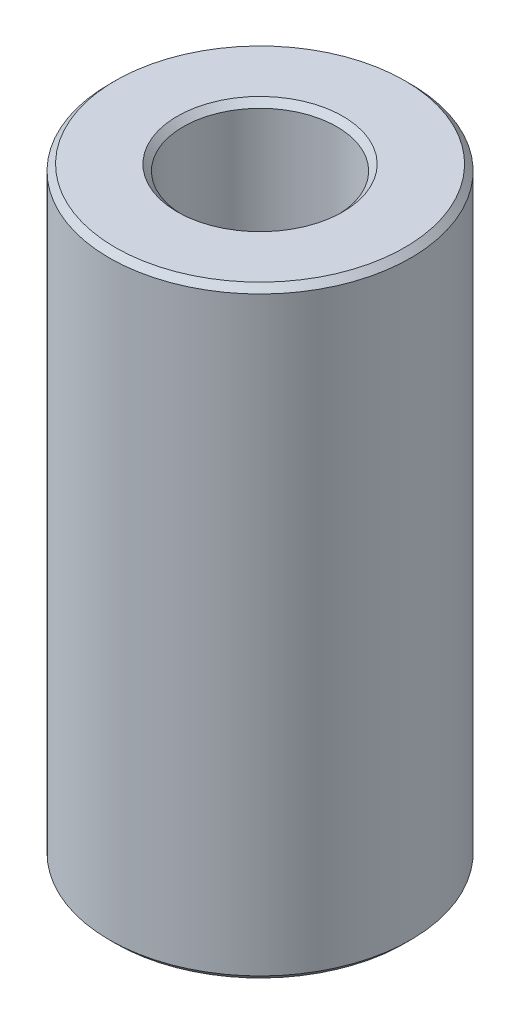
SolidWorks part; units mm, degrees
material "6061-T6 (SS)"
ref_plane "Front Plane" through (0, 0, 0) normal (0, 0, 1) x (1, 0, 0)
ref_plane "Top Plane" through (0, 0, 0) normal (0, 1, 0) x (1, 0, 0)
ref_plane "Right Plane" through (0, 0, 0) normal (1, 0, 0) x (0, 0, -1)
sketch "Sketch1" plane through (0, 0, 0) normal (1, 0, 0) x (0, 0, -1)
  line L0 (0, 2.1339) -> (0, -2.1339) construction
  line L1 (2.55, 9.8) -> (2.75, 10)
  line L2 (2.75, 10) -> (4.8, 10)
  line L3 (2.55, 9.8) -> (2.55, -9.8)
  line L4 (2.75, -10) -> (4.8, -10)
  line L5 (5, 9.8) -> (5, -9.8)
  line L6 (2.55, 10) -> (5, -10) construction
  line L7 (2.55, -10) -> (5, 10) construction
  line L8 (4.8, 10) -> (5, 9.8)
  line L9 (4.8, -10) -> (5, -9.8)
  line L10 (2.55, -9.8) -> (2.75, -10)
  point P0 (3.775, 0)
  point P4 (0, 0)
  dimension "D1" = 2.45
  dimension "D2" = 20
  dimension "D3" = 2.55
revolve "Revolve1" add sketch "Sketch1" angle 360 about L0
